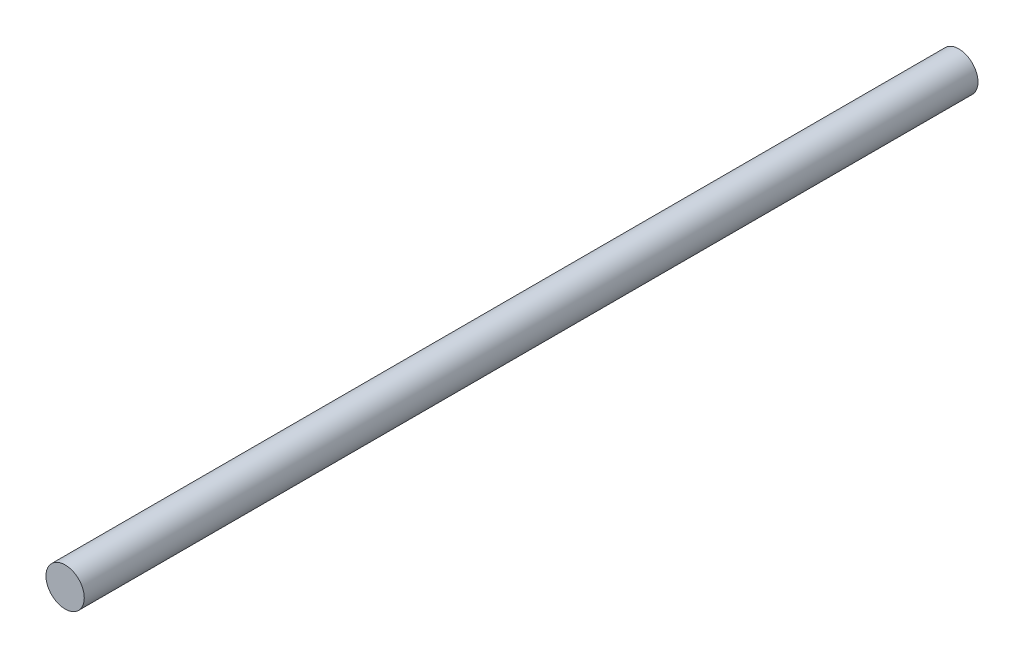
SolidWorks part; units mm, degrees
material "1.7036 (28CrS4)"
ref_plane "정면" through (0, 0, 0) normal (0, 0, 1) x (1, 0, 0)
ref_plane "윗면" through (0, 0, 0) normal (0, 1, 0) x (1, 0, 0)
ref_plane "우측면" through (0, 0, 0) normal (1, 0, 0) x (0, 0, -1)
sketch "스케치1" plane through (0, 0, 0) normal (0, 0, 1) x (1, 0, 0)
  circle A0 centre (0, 0) radius 7.5
  dimension "D1" = 15
extrude "보스-돌출1" add sketch "스케치1" along normal blind 350
